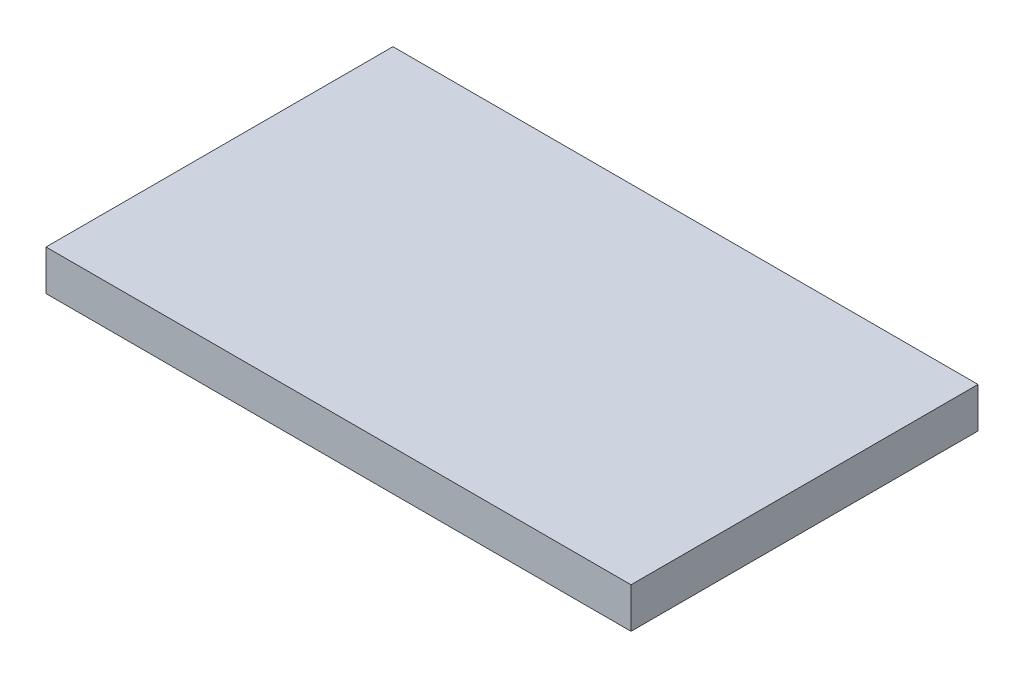
SolidWorks part; units mm, degrees
ref_plane "Front Plane" through (0, 0, 0) normal (0, 0, 1) x (1, 0, 0)
ref_plane "Top Plane" through (0, 0, 0) normal (0, 1, 0) x (1, 0, 0)
ref_plane "Right Plane" through (0, 0, 0) normal (1, 0, 0) x (0, 0, -1)
sketch "Sketch1" plane through (0, 0, 0) normal (0, 1, 0) x (1, 0, 0)
  line L1 (0, 0) -> (145, 0)
  line L2 (0, 0) -> (0, 86)
  line L3 (0, 86) -> (145, 86)
  line L4 (145, 0) -> (145, 86)
  line L5 (0, 0) -> (145, 86) construction
  line L6 (0, 86) -> (145, 0) construction
  point P4 (72.5, 43)
  dimension "D1" = 86
  dimension "D2" = 145
extrude "Boss-Extrude1" add sketch "Sketch1" along normal blind 10
